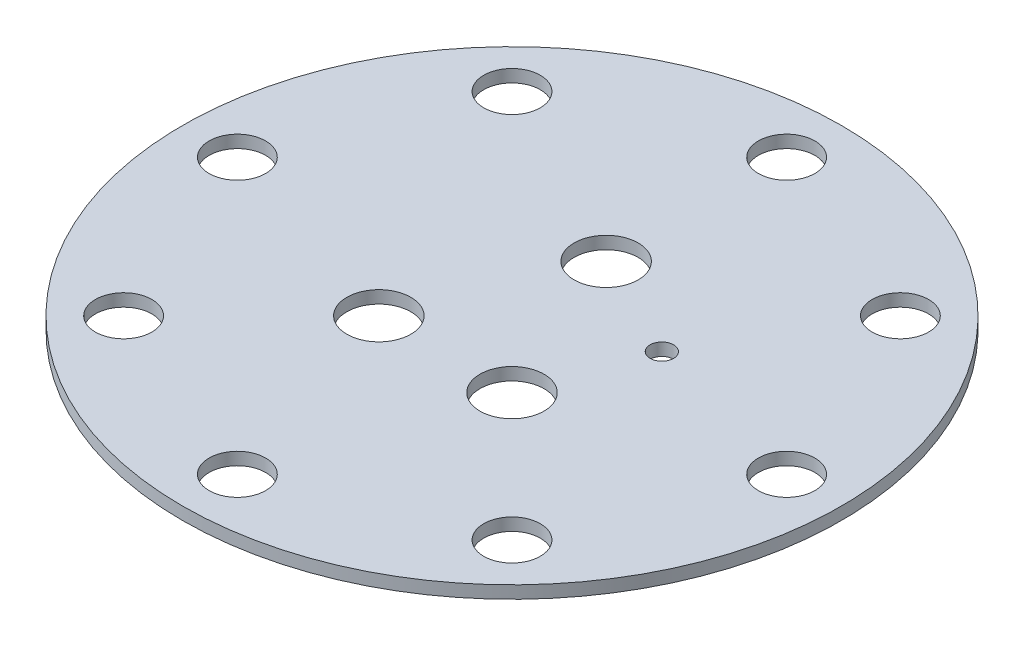
SolidWorks part; units mm, degrees
ref_plane "Front Plane" through (0, 0, 0) normal (0, 0, 1) x (1, 0, 0)
ref_plane "Top Plane" through (0, 0, 0) normal (0, 1, 0) x (1, 0, 0)
ref_plane "Right Plane" through (0, 0, 0) normal (1, 0, 0) x (0, 0, -1)
sketch "Sketch2" plane through (0, 0, 0) normal (0, 1, 0) x (1, 0, 0)
  line L0 (0, 0) -> (0, 105) construction
  line L1 (0, 0) -> (145.9568, 0) construction
  line L2 (0, 0) -> (148.1275, 61.3564) construction
  circle A0 centre (0, 0) radius 105
  circle A1 centre (0, 87.5) radius 9
  circle A2 centre (61.8718, 61.8718) radius 9
  circle A3 centre (0, 30) radius 10.2
  circle A4 centre (87.5, 0) radius 9
  circle A5 centre (61.8718, -61.8718) radius 9
  circle A6 centre (0, -87.5) radius 9
  circle A7 centre (-61.8718, -61.8718) radius 9
  circle A8 centre (-87.5, 0) radius 9
  circle A9 centre (-61.8718, 61.8718) radius 9
  circle A12 centre (0, 0) radius 50
  circle A13 centre (0, 30) radius 14.5
  circle A14 centre (21.2132, -21.2132) radius 10.2
  circle A15 centre (21.2132, -21.2132) radius 14.5
  circle A16 centre (33.7601, 13.9839) radius 3.75
  circle A17 centre (33.7601, 13.9839) radius 7
  circle A18 centre (-21.2132, -21.2132) radius 14.5
  circle A19 centre (-21.2132, -21.2132) radius 10.2
  point P3 (0, 87.5)
  point P8 (0, 0)
  point P11 (0, 30)
  point P23 (0, 0)
  point P29 (0, 0)
  point P30 (0, 0)
  point P33 (-0.9401, 2.5354)
  point P34 (0, 0)
  point P36 (0.9401, 2.5354)
  point P44 (0, 0)
  point P47 (0, 0)
  dimension "D1" = 210
  dimension "D4" = 18
  dimension "D5" = 100
  dimension "D7" = 20.4
  dimension "D8" = 29
  dimension "D9" = 2
  dimension "D14" = 7.5
  dimension "D15" = 14
  dimension "D2" = 17.5
  dimension "D6" = 30
  dimension "D13" = 22.5
  dimension "D3" = 8
  dimension "D10" = 2
sketch "Sketch3" plane through (0, 0, 0) normal (0, 1, 0) x (1, 0, 0)
  circle A5 centre (0, 30) radius 10.2
  circle A6 centre (0, 30) radius 10.2
  circle A7 centre (61.8718, 61.8718) radius 9
  circle A8 centre (61.8718, 61.8718) radius 9
  circle A9 centre (0, 87.5) radius 9
  circle A10 centre (0, 87.5) radius 9
  circle A11 centre (0, 0) radius 105
  circle A12 centre (0, 0) radius 105
  circle A13 centre (-61.8718, 61.8718) radius 9
  circle A14 centre (-61.8718, 61.8718) radius 9
  circle A15 centre (-87.5, 0) radius 9
  circle A16 centre (-87.5, 0) radius 9
  circle A17 centre (-61.8718, -61.8718) radius 9
  circle A18 centre (-61.8718, -61.8718) radius 9
  circle A19 centre (0, -87.5) radius 9
  circle A20 centre (0, -87.5) radius 9
  circle A21 centre (61.8718, -61.8718) radius 9
  circle A22 centre (61.8718, -61.8718) radius 9
  circle A23 centre (87.5, 0) radius 9
  circle A24 centre (87.5, 0) radius 9
  circle A25 centre (-21.2132, -21.2132) radius 10.2
  circle A26 centre (-21.2132, -21.2132) radius 10.2
  circle A31 centre (33.7601, 13.9839) radius 3.75
  circle A32 centre (33.7601, 13.9839) radius 3.75
  circle A35 centre (21.2132, -21.2132) radius 10.2
  circle A36 centre (21.2132, -21.2132) radius 10.2
  dimension "D3" = 0
  dimension "D4" = 0
  dimension "D5" = 0
  dimension "D6" = 0
  dimension "D7" = 0
  dimension "D8" = 0
  dimension "D9" = 0
  dimension "D10" = 0
  dimension "D11" = 0
  dimension "D12" = 0
  dimension "D13" = 0
  dimension "D16" = 0
  dimension "D18" = 0
extrude "Boss-Extrude1" add sketch "Sketch3" along normal blind 4
